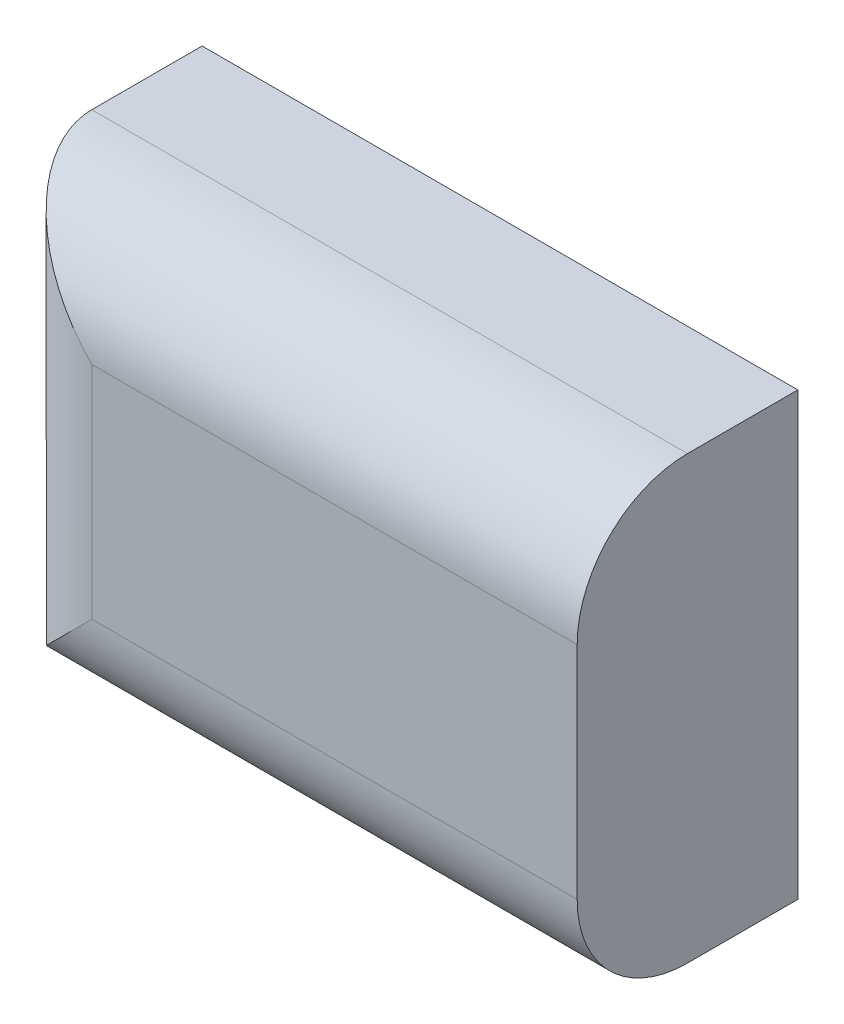
SolidWorks part; units mm, degrees
material "PE Low/Medium Density"
ref_plane "Front Plane" through (0, 0, 0) normal (0, 0, 1) x (1, 0, 0)
ref_plane "Top Plane" through (0, 0, 0) normal (0, 1, 0) x (1, 0, 0)
ref_plane "Right Plane" through (0, 0, 0) normal (1, 0, 0) x (0, 0, -1)
sketch "Sketch1" plane through (0, 0, 0) normal (1, 0, 0) x (0, 0, -1)
  line L0 (-37.5168, -42.1411) -> (25.9832, -42.1411)
  line L1 (-37.5168, -42.1411) -> (-37.5168, 84.8589)
  line L2 (25.9832, 84.8589) -> (-37.5168, 84.8589)
  line L4 (25.9832, 84.8589) -> (25.9832, -42.1411)
  point P7 (-37.5168, -42.1411)
  point P10 (-37.5168, 84.8589)
  dimension "D1" = 63.5
  dimension "D2" = 127
extrude "Boss-Extrude1" add sketch "Sketch1" along normal blind 171.45
fillet "Fillet1" radius 31.75 3 edges at (0, 21.3589, 37.5168) (85.725, -42.1411, 37.5168) (85.725, 84.8589, 37.5168)
